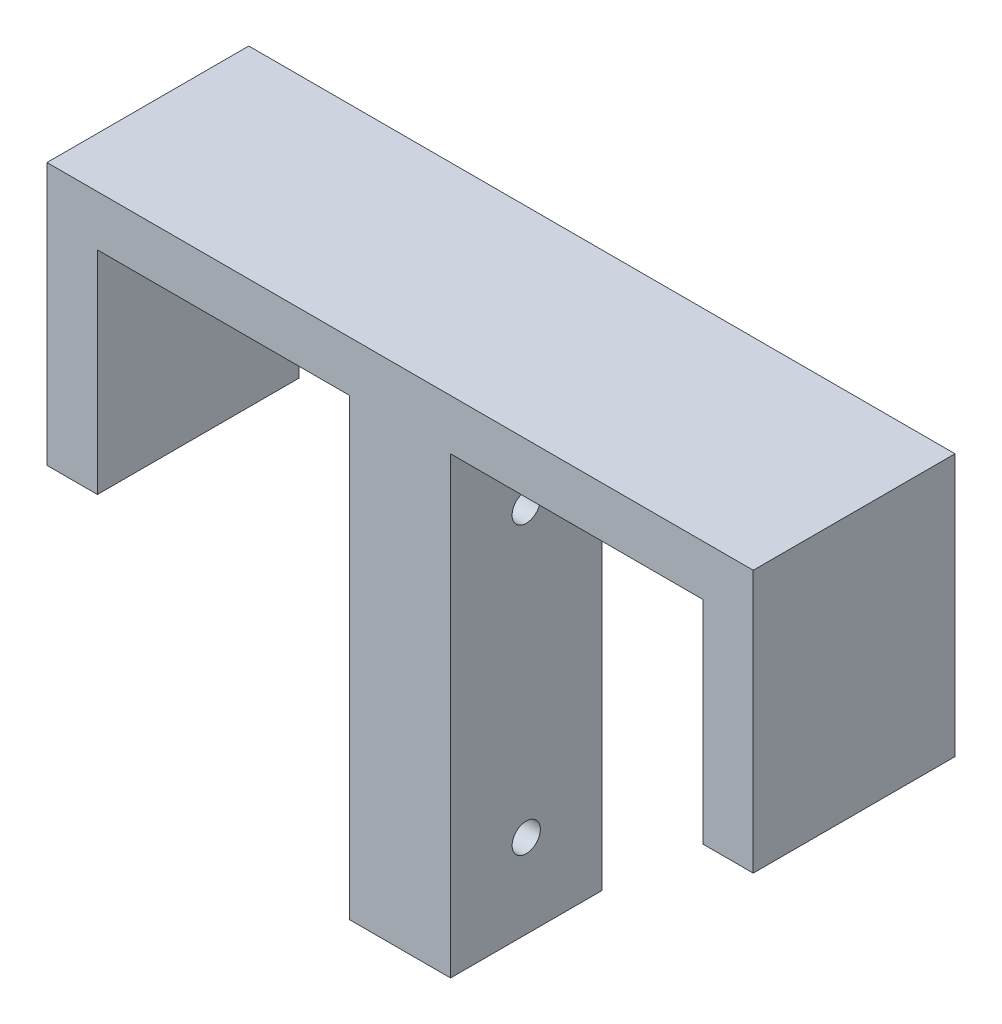
SolidWorks part; units mm, degrees
ref_plane "Front Plane" through (0, 0, 0) normal (0, 0, 1) x (1, 0, 0)
ref_plane "Top Plane" through (0, 0, 0) normal (0, 1, 0) x (1, 0, 0)
ref_plane "Right Plane" through (0, 0, 0) normal (1, 0, 0) x (0, 0, -1)
sketch "Sketch1" plane through (0, 0, 0) normal (0, 0, 1) x (1, 0, 0)
  line L4 (-3.175, -14.2875) -> (3.175, -14.2875)
  line L5 (-3.175, -14.2875) -> (-3.175, 14.2875)
  line L6 (-3.175, 14.2875) -> (3.175, 14.2875)
  line L7 (3.175, -14.2875) -> (3.175, 14.2875)
  line L8 (-3.175, -14.2875) -> (3.175, 14.2875) construction
  line L9 (-3.175, 14.2875) -> (3.175, -14.2875) construction
  point P0 (0, 0)
  dimension "D1" = 28.575
  dimension "D2" = 6.35
extrude "Boss-Extrude1" add sketch "Sketch1" along normal blind 9.525
sketch "Sketch3" plane through (0, 0, 9.525) normal (0, 0, 1) x (1, 0, 0)
  line L0 (3.175, 14.2875) -> (-3.175, 14.2875) construction
  line L1 (-22.225, 17.4625) -> (22.225, 17.4625)
  line L2 (-22.225, 17.4625) -> (-22.225, 14.2875)
  line L3 (-22.225, 14.2875) -> (22.225, 14.2875)
  line L4 (22.225, 17.4625) -> (22.225, 14.2875)
  line L5 (-22.225, 17.4625) -> (22.225, 14.2875) construction
  line L6 (-22.225, 14.2875) -> (22.225, 17.4625) construction
  line L7 (0, 15.875) -> (0, -0.3196) construction
  line L8 (-22.225, 14.2875) -> (-19.05, 14.2875)
  line L9 (-22.225, 14.2875) -> (-22.225, 0.9525)
  line L10 (-22.225, 0.9525) -> (-19.05, 0.9525)
  line L11 (-19.05, 14.2875) -> (-19.05, 0.9525)
  line L12 (22.225, 0.9525) -> (19.05, 0.9525)
  line L13 (19.05, 14.2875) -> (19.05, 0.9525)
  line L14 (22.225, 14.2875) -> (19.05, 14.2875)
  line L15 (22.225, 14.2875) -> (22.225, 0.9525)
  point P0 (0, 15.875)
  line M14 (3.175, 14.2875) -> (-3.175, 14.2875)
  dimension "D1" = 3.175
  dimension "D2" = 44.45
  dimension "D3" = 13.335
  dimension "D4" = 3.175
extrude "Boss-Extrude2" add sketch "Sketch3" against normal blind 12.7 contours L11 L3 L9 L10 | L4 L1 L2 L3 M14 | L15 L3 L13 L12
sketch "Sketch4" plane through (3.175, 0, 0) normal (1, 0, 0) x (0, 0, -1)
  line L0 (-9.525, 0) -> (0, 0) construction
  line L1 (-9.525, -14.2875) -> (-9.525, 14.2875) construction
  line L2 (-4.7625, 9.0043) -> (-4.7625, -9.0043) construction
  circle A0 centre (-4.7625, -9.0043) radius 0.889
  circle A1 centre (-4.7625, 9.0043) radius 0.889
  point P10 (-4.7625, 0)
  dimension "D2" = 1.778
  dimension "D1" = 9.0043
extrude "Cut-Extrude1" cut sketch "Sketch4" against normal up to next
